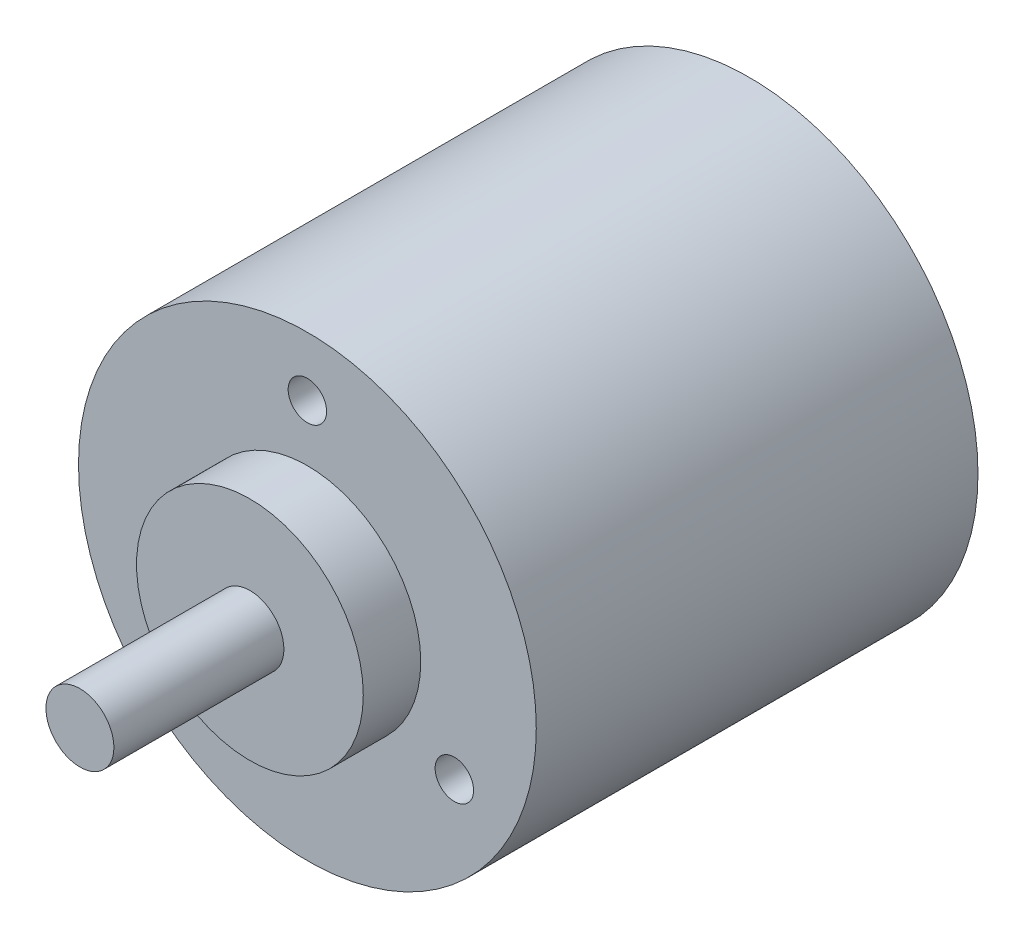
SolidWorks part; units mm, degrees
ref_plane "Front Plane" through (0, 0, 0) normal (0, 0, 1) x (1, 0, 0)
ref_plane "Top Plane" through (0, 0, 0) normal (0, 1, 0) x (1, 0, 0)
ref_plane "Right Plane" through (0, 0, 0) normal (1, 0, 0) x (0, 0, -1)
sketch "Sketch1" plane through (0, 0, 0) normal (0, 0, 1) x (1, 0, 0)
  circle A0 centre (0, 0) radius 20.2311
  dimension "D1" = 40.4622
extrude "Boss-Extrude1" add sketch "Sketch1" along normal mid plane 39.0398
sketch "Sketch2" plane through (0, 0, 19.5199) normal (0, 0, 1) x (1, 0, 0)
  circle A0 centre (0, 0) radius 10.0203
  dimension "D1" = 20.0406
extrude "Boss-Extrude2" add sketch "Sketch2" along normal blind 5.08
sketch "Sketch3" plane through (0, 0, 24.5999) normal (0, 0, 1) x (1, 0, 0)
  circle A0 centre (0, 0) radius 3.0035
  dimension "D1" = 6.0071
extrude "Boss-Extrude3" add sketch "Sketch3" along normal blind 15.0241
hole_wizard "M3 Clearance Hole1" positions "Sketch5" profile "Sketch4" hole size "M3" standard "ANSI Metric"
sketch "Sketch5" plane through (0, 0, 19.5199) normal (0, 0, 1) x (1, 0, 0)
  circle A0 centre (0, 0) radius 15 construction
  point P8 (0, 15)
  point P20 (12.9904, -7.5)
  point P21 (-12.9904, -7.5)
  point P22 (0, 0)
  dimension "D1" = 30
  dimension "D2" = 3
sketch "Sketch4" plane through (0, 15, 19.5199) normal (1, 0, 0) x (0, -1, 0)
  line L0 (0, 0) -> (0, 8.0215)
  line L1 (0, 8.0215) -> (1.7, 7)
  line L2 (1.7, 7) -> (1.7, 0)
  line L5 (1.7, 0) -> (0, 0)
  line L10 (0, 8.0215) -> (-1.7, 7) construction
  line L11 (0, -6.35) -> (0, 107.95) construction
  dimension "Hole Dia." = 3.4
  dimension "Hole Depth" = 7
  dimension "Drill Angle" = 118
